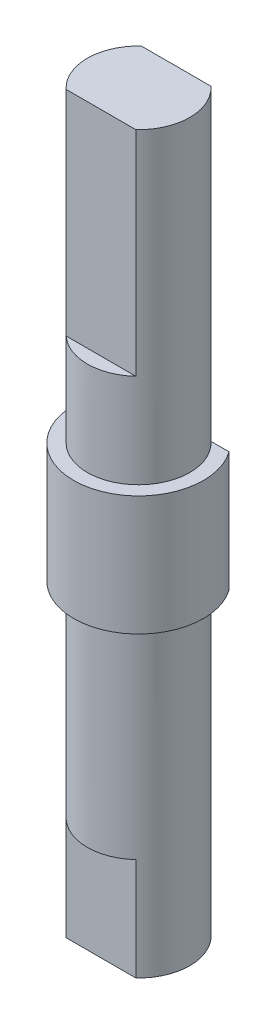
SolidWorks part; units mm, degrees
ref_plane "Front Plane" through (0, 0, 0) normal (0, 0, 1) x (1, 0, 0)
ref_plane "Top Plane" through (0, 0, 0) normal (0, 1, 0) x (1, 0, 0)
ref_plane "Right Plane" through (0, 0, 0) normal (1, 0, 0) x (0, 0, -1)
sketch "Sketch1" plane through (0, 0, 0) normal (0, 1, 0) x (1, 0, 0)
  circle A0 centre (0, 0) radius 1.9
  dimension "D1" = 3.8
extrude "Boss-Extrude1" add sketch "Sketch1" along normal mid plane 3.5
sketch "Sketch2" plane through (0, -1.75, 0) normal (0, -1, 0) x (1, 0, 0)
  circle A0 centre (0, 0) radius 1.5
extrude "Boss-Extrude2" add sketch "Sketch2" along normal blind 9
sketch "Sketch4" plane through (0, 1.75, 0) normal (0, 1, 0) x (1, 0, 0)
  circle A0 centre (0, 0) radius 1.5
  dimension "D1" = 3
extrude "Boss-Extrude3" add sketch "Sketch4" along normal blind 9
sketch "Sketch3" plane through (0, 0, 0) normal (0, 1, 0) x (1, 0, 0)
  line L0 (-1.5492, 1.1) -> (1.5492, 1.1)
  arc A0 (1.5492, 1.1) -> (-1.5492, 1.1) centre (0, 0) ccw
  arc A1 (-1.5492, 1.1) -> (1.5492, 1.1) centre (0, 0) ccw construction
  dimension "D1" = 3.8
  dimension "D2" = 1.1
extrude "Cut-Extrude1" cut sketch "Sketch3" against normal through all both and the other way through all
sketch "Sketch5" plane through (0, 10.75, 0) normal (0, 1, 0) x (1, 0, 0)
  line L0 (1.0198, -1.1) -> (-1.0198, -1.1)
  arc A2 (-1.0198, 1.1) -> (1.0198, 1.1) centre (0, 0) ccw construction
  arc A3 (-1.0198, -1.1) -> (1.0198, -1.1) centre (0, 0) ccw
  dimension "D1" = 1.1
extrude "Cut-Extrude2" cut sketch "Sketch5" against normal blind 6.25
sketch "Sketch6" plane through (0, -10.75, 0) normal (0, -1, 0) x (1, 0, 0)
  line L0 (-1.0198, 1.1) -> (1.0198, 1.1)
  arc A0 (1.0198, -1.1) -> (-1.0198, -1.1) centre (0, 0) ccw construction
  arc A1 (-1.0198, 1.1) -> (1.0198, 1.1) centre (0, 0) cw
  dimension "D1" = 1.1
extrude "Cut-Extrude3" cut sketch "Sketch6" against normal blind 3
